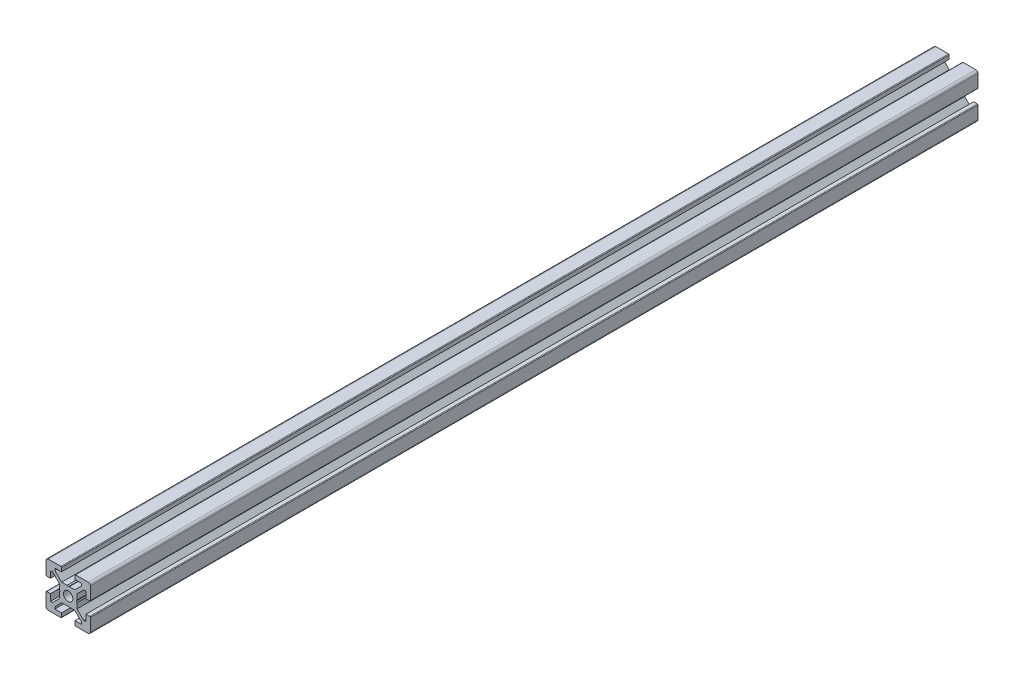
SolidWorks part; units mm, degrees
ref_plane "前基準面" through (0, 0, 0) normal (0, 0, 1) x (1, 0, 0)
ref_plane "上基準面" through (0, 0, 0) normal (0, 1, 0) x (1, 0, 0)
ref_plane "右基準面" through (0, 0, 0) normal (1, 0, 0) x (0, 0, -1)
ref_plane "平面1" through (0, 0, 0) normal (0, 0, 1) x (1, 0, 0)
sketch "草圖1" plane through (0, 0, 0) normal (0, 0, 1) x (1, 0, 0)
  line L0 (-10, 9) -> (-10, 3.3)
  line L1 (-9.7, 3) -> (-8, 3)
  line L2 (-8, 3) -> (-8, 6)
  line L3 (-8, 6) -> (-7.0607, 6)
  line L4 (-7.0607, 6) -> (-4, 2.9393)
  line L5 (-4, 2.9393) -> (-4, 0.5196)
  line L6 (-4, 0.5196) -> (-3.7, 0)
  line L7 (-3.7, 0) -> (-4, -0.5196)
  line L8 (-4, -0.5196) -> (-4, -2.9393)
  line L9 (-4, -2.9393) -> (-7.0607, -6)
  line L10 (-7.0607, -6) -> (-8, -6)
  line L11 (-8, -6) -> (-8, -3)
  line L12 (-8, -3) -> (-9.7, -3)
  line L13 (-10, -3.3) -> (-10, -9)
  line L14 (-9, -10) -> (-3.3, -10)
  line L15 (-3, -9.7) -> (-3, -8)
  line L16 (-3, -8) -> (-6, -8)
  line L17 (-6, -8) -> (-6, -7.0607)
  line L18 (-6, -7.0607) -> (-2.9393, -4)
  line L19 (-2.9393, -4) -> (-0.5196, -4)
  line L20 (-0.5196, -4) -> (0, -3.7)
  line L21 (0, -3.7) -> (0.5196, -4)
  line L22 (0.5196, -4) -> (2.9393, -4)
  line L23 (2.9393, -4) -> (6, -7.0607)
  line L24 (6, -7.0607) -> (6, -8)
  line L25 (6, -8) -> (3, -8)
  line L26 (3, -8) -> (3, -9.7)
  line L27 (3.3, -10) -> (9, -10)
  line L28 (10, -9) -> (10, -3.3)
  line L29 (9.7, -3) -> (8, -3)
  line L30 (8, -3) -> (8, -6)
  line L31 (8, -6) -> (7.0606, -6)
  line L32 (7.0606, -6) -> (4, -2.9393)
  line L33 (4, -2.9393) -> (4, -0.5196)
  line L34 (4, -0.5196) -> (3.7, 0)
  line L35 (3.7, 0) -> (4, 0.5196)
  line L36 (4, 0.5196) -> (4, 2.9393)
  line L37 (4, 2.9393) -> (7.0607, 6)
  line L38 (7.0607, 6) -> (8, 6)
  line L39 (8, 6) -> (8, 3)
  line L40 (8, 3) -> (9.7, 3)
  line L41 (10, 3.3) -> (10, 9)
  line L42 (9, 10) -> (3.3, 10)
  line L43 (3, 9.7) -> (3, 8)
  line L44 (3, 8) -> (6, 8)
  line L45 (6, 8) -> (6, 7.0607)
  line L46 (6, 7.0607) -> (2.9393, 4)
  line L47 (2.9393, 4) -> (0.5196, 4)
  line L48 (0.5196, 4) -> (0, 3.7)
  line L49 (0, 3.7) -> (-0.5196, 4)
  line L50 (-0.5196, 4) -> (-2.9394, 4)
  line L51 (-2.9394, 4) -> (-6, 7.0606)
  line L52 (-6, 7.0606) -> (-6, 8)
  line L53 (-6, 8) -> (-3, 8)
  line L54 (-3, 8) -> (-3, 9.7)
  line L55 (-3.3, 10) -> (-9, 10)
  arc A0 (-10, 3.3) -> (-9.7, 3) centre (-9.7, 3.3) ccw
  arc A1 (-9.7, -3) -> (-10, -3.3) centre (-9.7, -3.3) ccw
  arc A2 (-10, -9) -> (-9, -10) centre (-9, -9) ccw
  arc A3 (-3.3, -10) -> (-3, -9.7) centre (-3.3, -9.7) ccw
  arc A4 (3, -9.7) -> (3.3, -10) centre (3.3, -9.7) ccw
  arc A5 (9, -10) -> (10, -9) centre (9, -9) ccw
  arc A6 (10, -3.3) -> (9.7, -3) centre (9.7, -3.3) ccw
  arc A7 (9.7, 3) -> (10, 3.3) centre (9.7, 3.3) ccw
  arc A8 (10, 9) -> (9, 10) centre (9, 9) ccw
  arc A9 (3.3, 10) -> (3, 9.7) centre (3.3, 9.7) ccw
  arc A10 (-3, 9.7) -> (-3.3, 10) centre (-3.3, 9.7) ccw
  arc A11 (-9, 10) -> (-10, 9) centre (-9, 9) ccw
extrude "填料-伸長1" add sketch "草圖1" against normal blind 400
ref_plane "平面2" through (0, 0, 0) normal (1, 0, 0) x (0, 0, -1)
sketch "草圖2" plane through (0, 0, 0) normal (1, 0, 0) x (0, 0, -1)
  line L0 (0, 0) -> (0, 2.1)
  line L1 (0, 2.1) -> (400, 2.1)
  line L2 (400, 2.1) -> (400, 0)
  line L3 (400, 0) -> (0, 0)
  line L4 (400, 0) -> (0, 0) construction
revolve "除料-旋轉1" cut sketch "草圖2" angle 360 about L4
